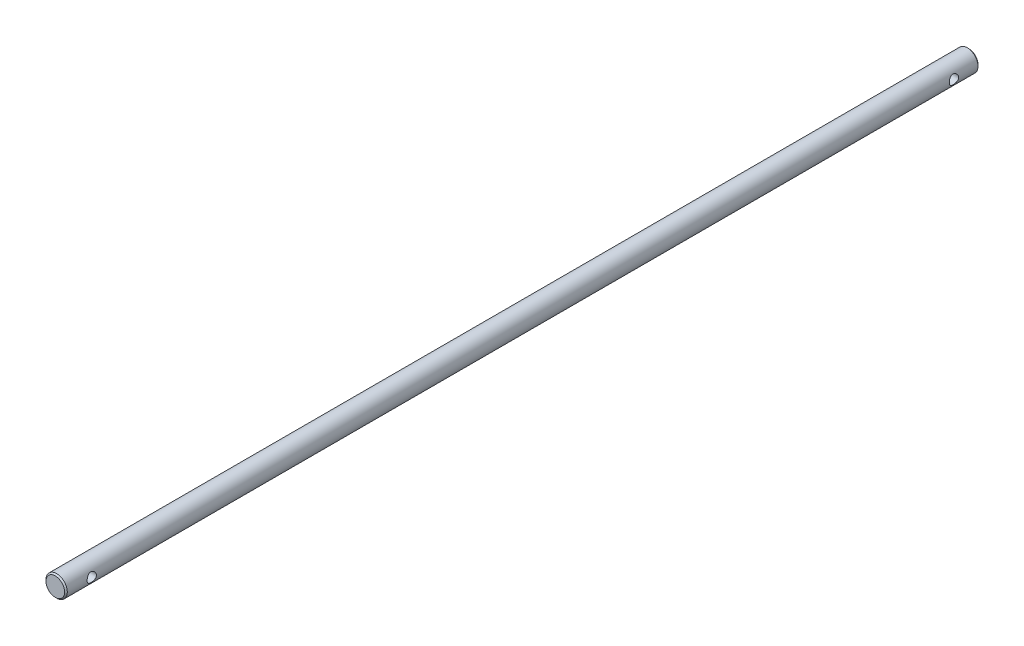
SolidWorks part; units mm, degrees
ref_plane "Front Plane" through (0, 0, 0) normal (0, 0, 1) x (1, 0, 0)
ref_plane "Top Plane" through (0, 0, 0) normal (0, 1, 0) x (1, 0, 0)
ref_plane "Right Plane" through (0, 0, 0) normal (1, 0, 0) x (0, 0, -1)
sketch "Sketch1" plane through (0, 0, 0) normal (0, 0, 1) x (1, 0, 0)
  circle A0 centre (0, 0) radius 4
  dimension "D1" = 8
extrude "Boss-Extrude1" add sketch "Sketch1" along normal blind 342.9
chamfer "Chamfer1" distance 0.5 angle 45 2 edges at (4, 0, 0) (4, 0, 342.9)
sketch "Sketch2" plane through (0, 0, 0) normal (0, 0, -1) x (-1, 0, 0)
  line L0 (-3.5, 0) -> (3.5, 0) construction
  circle A0 centre (0, 0) radius 3.5 construction
ref_plane "Plane1" through (-4, 0, 0) normal (-1, 0, 0) x (0, 0, 1)
sketch "Sketch3" plane through (-4, 0, 0) normal (-1, 0, 0) x (0, 0, 1)
  line L0 (0, 0) -> (342.714, 0) construction
  line L1 (171.357, 0) -> (171.357, -4.9674) construction
  circle A0 centre (9.525, 0) radius 1.7526
  circle A1 centre (333.189, 0) radius 1.7526
  dimension "D1" = 3.5052
  dimension "D2" = 9.525
extrude "Cut-Extrude1" cut sketch "Sketch3" against normal through all
